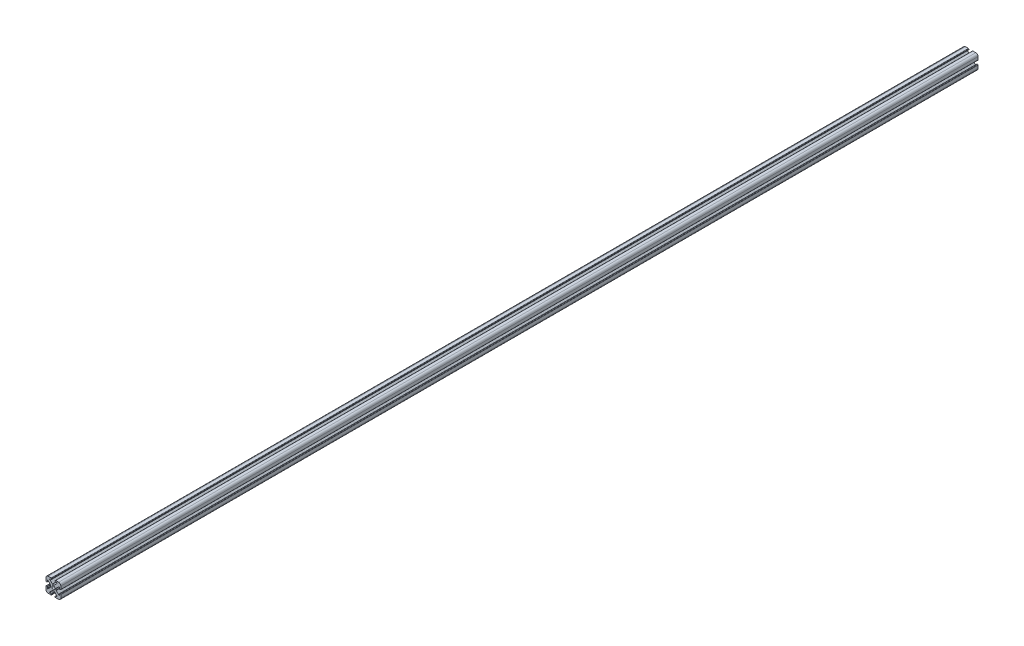
SolidWorks part; units mm, degrees
ref_plane "Front Plane" through (0, 0, 0) normal (0, 0, 1) x (1, 0, 0)
ref_plane "Top Plane" through (0, 0, 0) normal (0, 1, 0) x (1, 0, 0)
ref_plane "Right Plane" through (0, 0, 0) normal (1, 0, 0) x (0, 0, -1)
sketch "Sketch1" plane through (0, 0, 0) normal (0, 0, 1) x (1, 0, 0)
  line L1 (-3.65, 3.65) -> (3.65, 3.65)
  line L2 (-3.65, 3.65) -> (-3.65, -3.65)
  line L3 (-3.65, -3.65) -> (3.65, -3.65)
  line L4 (3.65, 3.65) -> (3.65, -3.65)
  line L5 (-3.65, 3.65) -> (3.65, -3.65) construction
  line L6 (-3.65, -3.65) -> (3.65, 3.65) construction
  circle A0 centre (0, 0) radius 2.15
  point P0 (0, 0)
  dimension "D1" = 7.3
  dimension "D2" = 7.3
extrude "Boss-Extrude1" add sketch "Sketch1" along normal blind 1240
sketch "Sketch2" plane through (0, 0, 0) normal (0, 0, 1) x (1, 0, 0)
  line L0 (3.65, 3.65) -> (1.2, 3.65)
  line L1 (3.65, 3.65) -> (-3.65, 3.65) construction
  line L2 (3.65, -3.65) -> (3.65, 3.65) construction
  line L4 (3.65, 3.65) -> (3.65, 1.2)
  line L5 (1.2, 3.65) -> (5.75, 8.2)
  line L6 (3.65, 1.2) -> (8.2, 5.75)
  line L7 (8.2, 5.75) -> (8.2, 2.5)
  line L8 (5.75, 8.2) -> (2.5, 8.2)
  line L9 (8.2, 2.5) -> (10, 2.5)
  line L10 (2.5, 8.2) -> (2.5, 10)
  line L11 (2.5, 10) -> (10, 10)
  line L12 (10, 2.5) -> (10, 10)
  line L13 (-3.65, 3.65) -> (-1.2, 3.65)
  line L14 (-3.65, 3.65) -> (-3.65, 1.2)
  line L15 (-3.65, 3.65) -> (-3.65, -3.65) construction
  line L16 (-3.65, -3.65) -> (-3.65, -1.2)
  line L17 (-3.65, -3.65) -> (-1.2, -3.65)
  line L18 (-3.65, -3.65) -> (3.65, -3.65) construction
  line L19 (3.65, -3.65) -> (3.65, -1.2)
  line L20 (3.65, -3.65) -> (1.2, -3.65)
  line L21 (-3.65, -1.2) -> (-8.2, -5.75)
  line L22 (-1.2, -3.65) -> (-5.75, -8.2)
  line L23 (3.65, -1.2) -> (8.2, -5.75)
  line L24 (1.2, -3.65) -> (5.75, -8.2)
  line L25 (-1.2, 3.65) -> (-5.75, 8.2)
  line L26 (-3.65, 1.2) -> (-8.2, 5.75)
  line L27 (-5.75, 8.2) -> (-2.5, 8.2)
  line L28 (-8.2, 5.75) -> (-8.2, 2.5)
  line L29 (8.2, -5.75) -> (8.2, -2.5)
  line L30 (5.75, -8.2) -> (2.5, -8.2)
  line L31 (-5.75, -8.2) -> (-2.5, -8.2)
  line L32 (-8.2, -5.75) -> (-8.2, -2.5)
  line L33 (8.2, -2.5) -> (10, -2.5)
  line L34 (2.5, -8.2) -> (2.5, -10)
  line L35 (-2.5, -8.2) -> (-2.5, -10)
  line L36 (-8.2, -2.5) -> (-10, -2.5)
  line L37 (-8.2, 2.5) -> (-10, 2.5)
  line L38 (-2.5, 8.2) -> (-2.5, 10)
  line L39 (-2.5, 10) -> (-10, 10)
  line L40 (-10, 10) -> (-10, 2.5)
  line L41 (-10, -2.5) -> (-10, -10)
  line L42 (-10, -10) -> (-2.5, -10)
  line L43 (2.5, -10) -> (10, -10)
  line L44 (10, -10) -> (10, -2.5)
extrude "Boss-Extrude2" add sketch "Sketch2" along normal blind 1240
fillet "Fillet4" radius 3 4 edges at (-10, -10, 620) (-10, 10, 620) (10, 10, 620) (10, -10, 620)
fillet "Fillet5" radius 0.5 15 edges at (2.5, 10, 620) (2.5, 8.2, 620) (-2.5, 10, 620) (-2.5, 8.2, 620) (8.2, 2.5, 620) (-8.2, 2.5, 620) (10, 2.5, 620) (-8.2, -2.5, 620) (-2.5, -10, 620) (-2.5, -8.2, 620) (-10, 2.5, 620) (-10, -2.5, 620) (10, -2.5, 620) (8.2, -2.5, 620) (2.5, -8.2, 620)
fillet "Fillet6" radius 0.5 8 edges at (1.2, -3.65, 620) (-1.2, -3.65, 620) (3.65, -1.2, 620) (3.65, 1.2, 620) (-1.2, 3.65, 620) (1.2, 3.65, 620) (-3.65, -1.2, 620) (-3.65, 1.2, 620)
fillet "Fillet7" radius 0.5 8 edges at (8.2, -5.75, 620) (8.2, 5.75, 620) (-8.2, -5.75, 620) (5.75, 8.2, 620) (-5.75, -8.2, 620) (5.75, -8.2, 620) (-8.2, 5.75, 620) (-5.75, 8.2, 620)
sketch "Sketch5" plane through (-3.65, 0, 0) normal (-1, 0, 0) x (0, 0, 1)
  line L0 (1240, 0) -> (1230, 0) construction
  line L1 (1240, 0.9929) -> (1240, -0.9929) construction
  circle A0 centre (1230, 0) radius 2.15
  dimension "D1" = 10
extrude "Cut-Extrude3" cut sketch "Sketch5" against normal through all
sketch "Sketch6" plane through (3.65, 0, 0) normal (1, 0, 0) x (0, 0, -1)
  line L0 (-1240, 0) -> (-1230, 0) construction
  line L1 (-1240, -0.9929) -> (-1240, 0.9929) construction
  circle A0 centre (-1230, 0) radius 2.15
extrude "Cut-Extrude4" cut sketch "Sketch6" against normal through all
